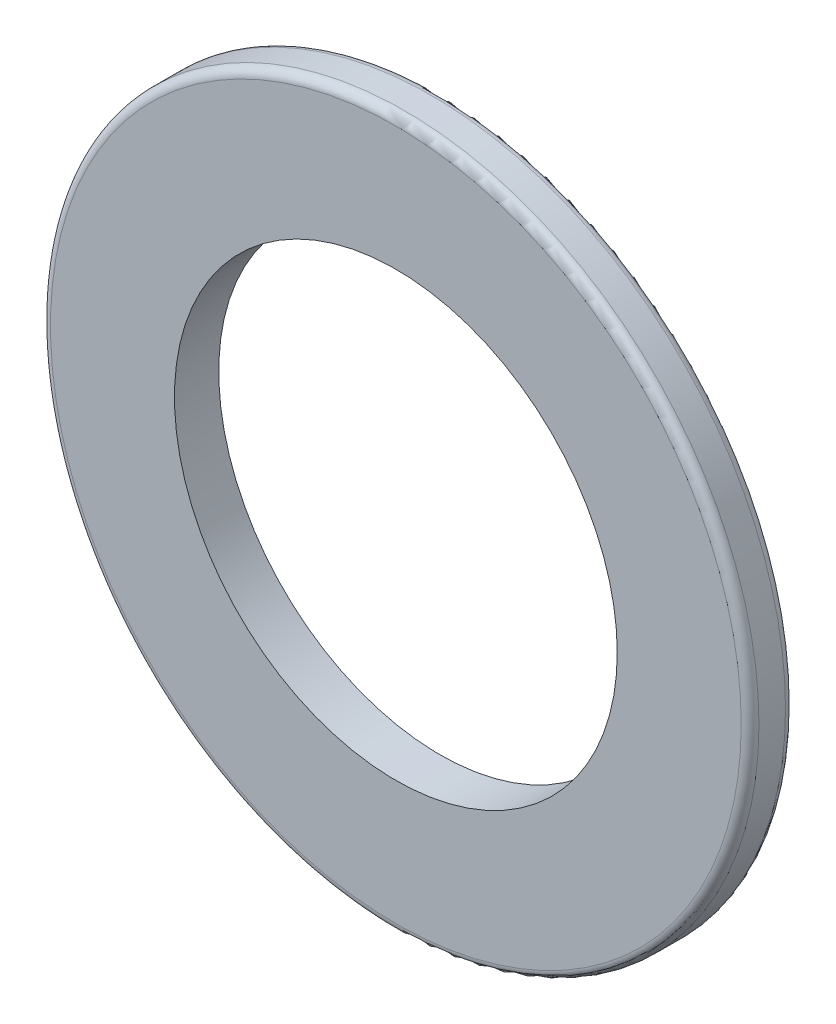
SolidWorks part; units mm, degrees
ref_plane "前视基准面" through (0, 0, 0) normal (0, 0, 1) x (1, 0, 0)
ref_plane "上视基准面" through (0, 0, 0) normal (0, 1, 0) x (1, 0, 0)
ref_plane "右视基准面" through (0, 0, 0) normal (1, 0, 0) x (0, 0, -1)
sketch "草图1" plane through (0, 0, 0) normal (0, 0, 1) x (1, 0, 0)
  line L0 (0, 0) -> (6.6675, 0) construction
  line L1 (0, 0) -> (0, 4.0944) construction
  circle A0 centre (0, 0) radius 4
  circle A1 centre (0, 0) radius 2.5
  dimension "D1" = 8
  dimension "D2" = 5
extrude "凸台-拉伸1" add sketch "草图1" along normal blind 0.5
fillet "圆角1" radius 0.1 2 edges at (4, 0, 0) (4, 0, 0.5)
